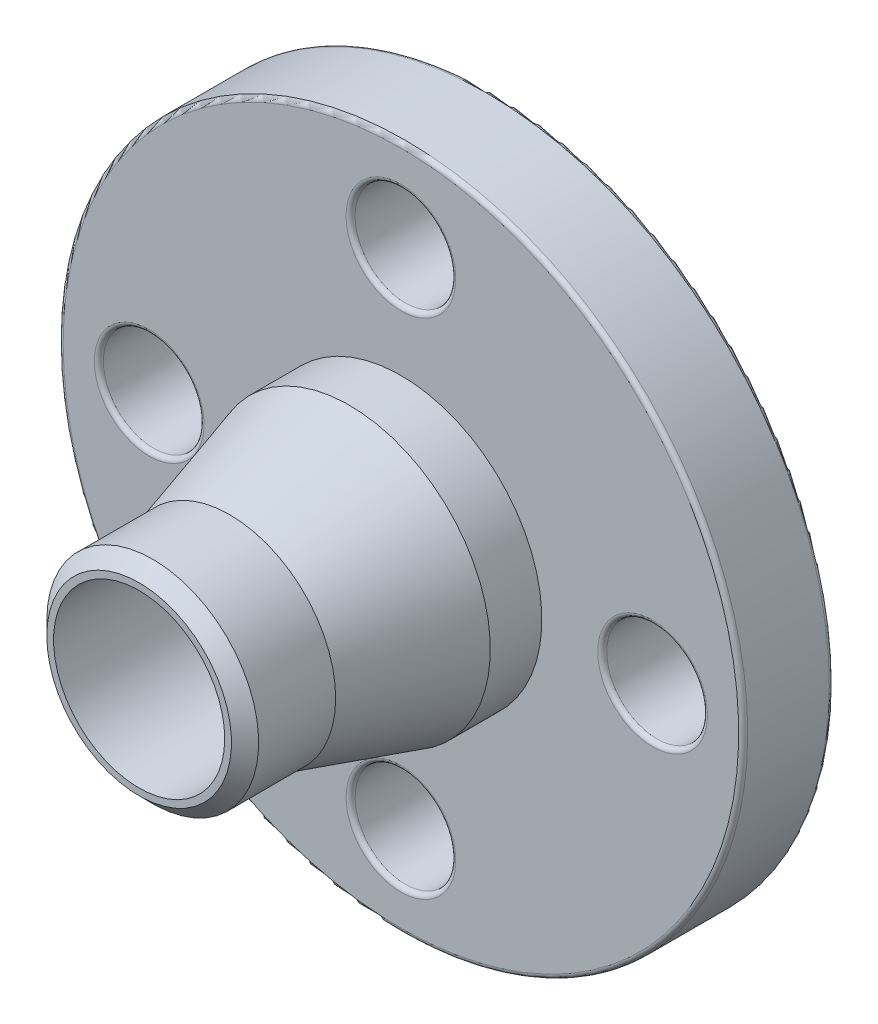
SolidWorks part; units mm, degrees
ref_plane "Front Plane" through (0, 0, 0) normal (0, 0, 1) x (1, 0, 0)
ref_plane "Top Plane" through (0, 0, 0) normal (0, 1, 0) x (1, 0, 0)
ref_plane "Right Plane" through (0, 0, 0) normal (1, 0, 0) x (0, 0, -1)
sketch "Sketch1" plane through (0, 0, 0) normal (1, 0, 0) x (0, 0, -1)
  line L0 (-27.7813, 0) -> (27.7813, 0) construction
  line L1 (27.7813, 13.4937) -> (27.7812, 53.975)
  line L2 (27.7812, 53.975) -> (13.4938, 53.975)
  line L3 (13.4938, 53.975) -> (13.4937, 24.6062)
  line L4 (13.4937, 24.6062) -> (-13.4938, 16.7005)
  line L5 (-13.4938, 16.7005) -> (-27.7812, 16.7005)
  line L6 (-27.7812, 16.7005) -> (-27.7813, 13.4937)
  line L7 (-27.7813, 13.4937) -> (27.7813, 13.4937)
  circle A0 centre (27.7813, 39.6875) radius 7.9375
  point P16 (27.7813, 39.6875)
  dimension "Bolt Size" = 15.875
  dimension "Flange OD" = 107.95
  dimension "Pipe Size" = 26.9875
  dimension "Hub at Chimney" = 33.401
  dimension "Hub OD Base" = 49.2125
  dimension "Flange Thickness" = 14.2875
  dimension "Length" = 55.5625
  dimension "Bolt O Diameter" = 79.375
sketch "Sketch2" plane through (0, 0, 0) normal (1, 0, 0) x (0, 0, -1)
  line L0 (-27.7812, 16.7005) -> (-27.7813, 13.4937) construction
  line L1 (-13.4938, 16.7005) -> (-27.7812, 16.7005) construction
  line L2 (13.4937, 24.6062) -> (-13.4938, 16.7005) construction
  line L3 (13.4938, 53.975) -> (13.4937, 24.6062) construction
  line L4 (27.7812, 53.975) -> (13.4938, 53.975) construction
  line L5 (27.7813, 13.4937) -> (27.7812, 53.975) construction
  line L6 (-27.7813, 13.4937) -> (27.7813, 13.4937) construction
  line L7 (-27.7812, 16.7005) -> (-27.7813, 13.4937)
  line L8 (-13.4938, 16.7005) -> (-27.7812, 16.7005)
  line L9 (13.4937, 24.6062) -> (-13.4938, 16.7005)
  line L10 (13.4938, 53.975) -> (13.4937, 24.6062)
  line L11 (27.7812, 53.975) -> (13.4938, 53.975)
  line L12 (27.7813, 13.4937) -> (27.7812, 53.975)
  line L13 (-27.7813, 13.4937) -> (27.7813, 13.4937)
revolve "Revolve1" add sketch "Sketch2" angle 360 about L0
sketch "Sketch3" plane through (0, 0, -13.4937) normal (0, 0, 1) x (1, 0, 0)
  line L0 (-13.4937, 0) -> (-16.7005, 0) construction
  circle A0 centre (0, 39.6875) radius 7.9375
  circle A1 centre (0, 0) radius 13.4937 construction
  circle A2 centre (0, 0) radius 16.7005 construction
  circle A5 centre (0, 0) radius 16.7005 construction
  dimension "D1" = 15.875
extrude "Cut-Extrude1" cut sketch "Sketch3" against normal through all
pattern_circular "CirPattern1" count 4 over 360 about axis through (0, 0, 0) along (0, 0, 1) of "Cut-Extrude1"
fillet "Fillet1" radius 2.8575 1 edges at (24.6062, 0, -13.4937)
chamfer "Chamfer1" distance 2.1431 angle 45 1 edges at (16.7005, 0, 27.7812)
fillet "Fillet2" radius 0.7144 11 edges at (53.975, 0, -27.7812) (53.975, 0, -13.4937) (13.4937, 0, -27.7813) (7.9375, 39.6875, -27.7813) (39.6875, -7.9375, -27.7813) (-39.6875, 7.9375, -27.7813) (-7.9375, -39.6875, -27.7813) (7.9375, 39.6875, -13.4937) (39.6875, -7.9375, -13.4937) (-39.6875, 7.9375, -13.4937) (-7.9375, -39.6875, -13.4937)
sketch "Sketch4" plane through (0, 0, 27.7813) normal (0, 0, 1) x (1, 0, 0)
  circle A0 centre (0, 0) radius 22.225
  circle A1 centre (0, 0) radius 68.8926
  dimension "D1" = 44.45
  dimension "D2" = 137.7852
extrude "Cut-Extrude2" cut sketch "Sketch4" against normal up to surface (41.275 mm away) up to face at (-53.2606, 0, -13.4937)
sketch "Sketch5" plane through (0, 0, -27.7813) normal (0, 0, -1) x (-1, 0, 0)
  circle A0 centre (0, 0) radius 22.225
  dimension "D1" = 44.45
extrude "Cut-Extrude3" cut sketch "Sketch5" against normal offset from surface (6.35 mm away) 6.35 up to face at (14.2081, 0, -27.7813)
equation "\"D1@Sketch3\"=\"bolt size@sketch1\""
equation "\"D1@Fillet1\"=\"Flange Thickness@Sketch1\"*0.2"
equation "\"D1@Chamfer1\"=\"Flange Thickness@Sketch1\"*0.15"
equation "\"D1@Fillet2\"=\"flange thickness@sketch1\"*0.05"
